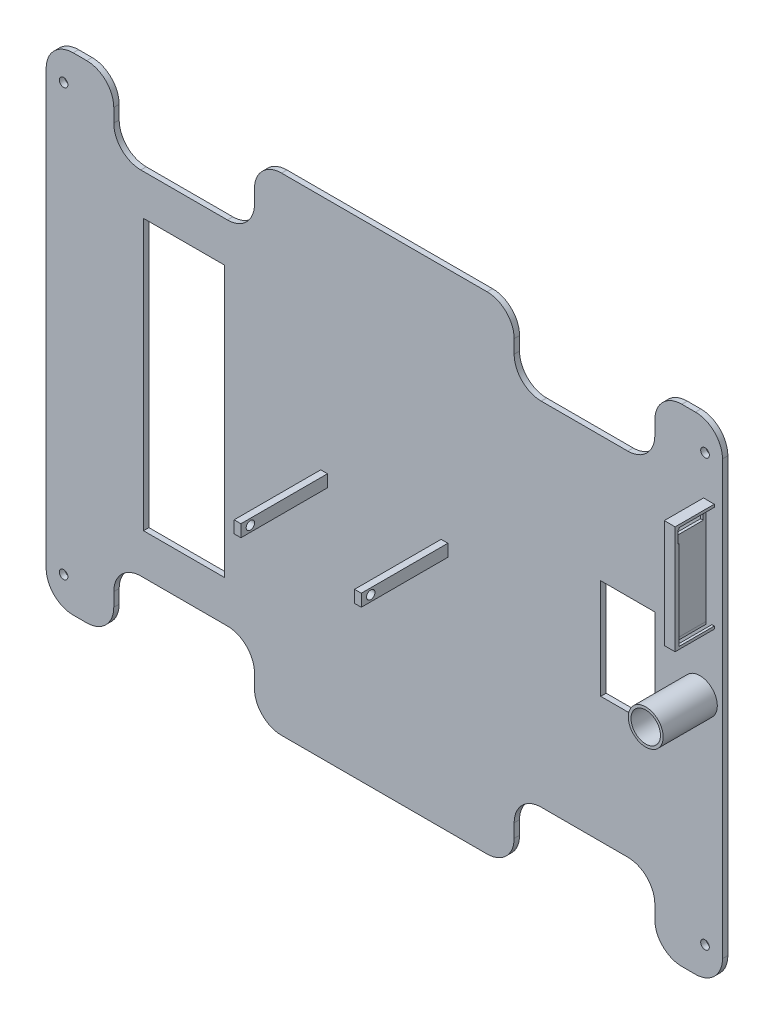
SolidWorks part; units mm, degrees
ref_plane "Plan de face" through (0, 0, 0) normal (0, 0, 1) x (1, 0, 0)
ref_plane "Plan de dessus" through (0, 0, 0) normal (0, 1, 0) x (1, 0, 0)
ref_plane "Plan de droite" through (0, 0, 0) normal (1, 0, 0) x (0, 0, -1)
sketch "Esquisse1" plane through (0, 0, 0) normal (0, 0, 1) x (1, 0, 0)
  line L0 (48, 77.5) -> (100, 77.5) construction
  line L1 (125, -90) -> (-125, -90)
  line L2 (125, -90) -> (125, 90)
  line L3 (125, 90) -> (-125, 90)
  line L4 (-125, -90) -> (-125, 90)
  line L5 (0, 90) -> (0, -90) construction
  line L6 (125, 0) -> (-125, 0) construction
  line L7 (-48, 65) -> (-100, 65)
  line L8 (-48, 65) -> (-48, 90)
  line L9 (-48, 90) -> (-100, 90)
  line L10 (-100, 65) -> (-100, 90)
  line L11 (-74, 90) -> (-74, 65) construction
  line L12 (-48, 77.5) -> (-100, 77.5) construction
  line L13 (74, 90) -> (74, 65) construction
  line L14 (100, 65) -> (100, 90)
  line L15 (48, 90) -> (100, 90)
  line L16 (48, 65) -> (48, 90)
  line L17 (48, 65) -> (100, 65)
  line L18 (74, -90) -> (74, -65) construction
  line L19 (-48, -77.5) -> (-100, -77.5) construction
  line L20 (-74, -90) -> (-74, -65) construction
  line L21 (48, -77.5) -> (100, -77.5) construction
  line L22 (48, -65) -> (100, -65)
  line L23 (48, -65) -> (48, -90)
  line L24 (48, -90) -> (100, -90)
  line L25 (100, -65) -> (100, -90)
  line L26 (-100, -65) -> (-100, -90)
  line L27 (-48, -90) -> (-100, -90)
  line L28 (-48, -65) -> (-48, -90)
  line L29 (-48, -65) -> (-100, -65)
  point P0 (0, 0)
  point P4 (-74, 77.5)
  point P16 (74, 77.5)
  point P33 (74, -77.5)
  point P34 (-74, -77.5)
  dimension "D1" = 250
  dimension "D2" = 180
  dimension "D3" = 52
  dimension "D4" = 25
  dimension "D5" = 25
extrude "Boss.-Extru.1" add sketch "Esquisse1" against normal blind 2 contours L2 L1 L4 L3 | L8 L7 L10 L9 | L14 L15 L16 L17 | L22 L25 L24 L23 | L26 L27 L28 L29
sketch "Esquisse2" plane through (0, 0, -2) normal (0, 0, -1) x (-1, 0, 0)
  line L1 (118.55, -78.76) -> (-118.55, -78.76) construction
  line L2 (118.55, -78.76) -> (118.55, 78.76) construction
  line L3 (118.55, 78.76) -> (-118.55, 78.76) construction
  line L4 (-118.55, -78.76) -> (-118.55, 78.76) construction
  line L5 (0, 78.76) -> (0, -78.76) construction
  line L6 (118.55, 0) -> (-118.55, 0) construction
  circle A0 centre (-118.55, 78.76) radius 1.6
  circle A1 centre (118.55, 78.76) radius 1.6
  circle A2 centre (118.55, -78.76) radius 1.6
  circle A3 centre (-118.55, -78.76) radius 1.6
  point P0 (0, 0)
  dimension "D3" = 3.2
  dimension "D1" = 237.1
  dimension "D2" = 157.52
extrude "Enlèv. mat.-Extru.1" cut sketch "Esquisse2" against normal through all
fillet "Congé1" radius 10 20 edges at (48, -90, -1) (48, -65, -1) (100, -65, -1) (100, -90, -1) (125, -90, -1) (125, 90, -1) (100, 90, -1) (100, 65, -1) (48, 65, -1) (48, 90, -1) (-48, 90, -1) (-48, 65, -1) (-100, 65, -1) (-100, 90, -1) (-125, -90, -1) (-100, -90, -1) (-100, -65, -1) (-48, -65, -1) (-48, -90, -1) (-125, 90, -1)
sketch "Esquisse3" plane through (0, 0, -2) normal (0, 0, -1) x (-1, 0, 0)
  circle A0 centre (122.8572, 0) radius 4.95
  dimension "D1" = 9.9
sketch "Esquisse5" plane through (0, 0, -2) normal (0, 0, -1) x (-1, 0, 0)
  line L0 (-125, -80) -> (-125, 80) construction
  line L1 (-80, -18.5) -> (-100, -18.5)
  line L2 (-80, -18.5) -> (-80, 18.5)
  line L3 (-80, 18.5) -> (-100, 18.5)
  line L4 (-100, -18.5) -> (-100, 18.5)
  line L5 (-90, 18.5) -> (-90, -18.5) construction
  line L6 (-80, 0) -> (-100, 0) construction
  point P0 (-90, 0)
  dimension "D1" = 37
  dimension "D2" = 20
  dimension "D3" = 35
extrude "Enlèv. mat.-Extru.4" cut sketch "Esquisse5" against normal blind 10
sketch "Esquisse6" plane through (0, 0, 0) normal (0, 0, 1) x (1, 0, 0)
  line L0 (125, -80) -> (125, 80) construction
  line L1 (122, 24) -> (118, 24)
  line L2 (122, 24) -> (122, 64)
  line L3 (122, 64) -> (118, 64)
  line L4 (118, 24) -> (118, 64)
  line L5 (120, 64) -> (120, 24) construction
  line L6 (122, 44) -> (118, 44) construction
  line L7 (58, 65) -> (90, 65) construction
  point P0 (120, 44)
  dimension "D1" = 40
  dimension "D2" = 4
  dimension "D3" = 5
  dimension "D4" = 1
extrude "Boss.-Extru.3" add sketch "Esquisse6" along normal blind 14.5
sketch "Esquisse9" plane through (122, 0, 0) normal (1, 0, 0) x (0, 0, -1)
  line L0 (-14.5, 24) -> (-14.5, 64) construction
  line L1 (0, 63) -> (-13, 63)
  line L2 (0, 63) -> (0, 25)
  line L3 (0, 25) -> (-13, 25)
  line L4 (-13, 63) -> (-13, 25)
  line L5 (-6.5, 25) -> (-6.5, 63) construction
  line L6 (0, 44) -> (-13, 44) construction
  line L7 (0, 24) -> (0, 64) construction
  point P0 (-6.5, 44)
  point P6 (-14.5, 44)
  point P7 (-7.25, 0.5)
  point P8 (-6.577, 0.5)
  point P9 (0, 0)
  point P12 (-7.25, 0.5)
  point P13 (-7.25, 0.5)
  point P14 (-7.25, 0.5)
  dimension "D1" = 38
  dimension "D2" = 1.5
sketch "Esquisse10" plane through (122, 0, 0) normal (1, 0, 0) x (0, 0, -1)
  line L0 (-14.5, 64) -> (0, 64) construction
  line L1 (-1.1, 57.9) -> (-13.4, 57.9)
  line L2 (-1.1, 57.9) -> (-1.1, 62.4)
  line L3 (-1.1, 62.4) -> (-13.4, 62.4)
  line L4 (-13.4, 57.9) -> (-13.4, 62.4)
  line L5 (-7.25, 62.4) -> (-7.25, 57.9) construction
  line L6 (-1.1, 60.15) -> (-13.4, 60.15) construction
  point P0 (-7.25, 60.15)
  point P6 (-7.25, 64)
  dimension "D1" = 12.3
  dimension "D2" = 38.4
  dimension "D3" = 4.5
  dimension "D4" = 3.85
extrude "Enlèv. mat.-Extru.5" cut sketch "Esquisse10" against normal blind 12.1 contours L1 L4 L3 L2
extrude "Enlèv. mat.-Extru.6" cut sketch "Esquisse9" against normal blind 3 contours L4 L3 L2 L1
sketch "Esquisse11" plane through (0, 25, 0) normal (0, 1, 0) x (1, 0, 0)
  line L0 (122, -14.5) -> (118, -14.5) construction
  line L1 (121.1, -13) -> (118.9, -13)
  line L2 (121.1, -13) -> (121.1, 0)
  line L3 (121.1, 0) -> (118.9, 0)
  line L4 (118.9, -13) -> (118.9, 0)
  line L5 (120, 0) -> (120, -13) construction
  line L6 (121.1, -6.5) -> (118.9, -6.5) construction
  line L7 (122, 0) -> (118, 0) construction
  point P0 (120, -6.5)
  point P6 (120, -14.5)
  point P7 (120, -6.6409)
  dimension "D1" = 13
  dimension "D2" = 2.2
extrude "Enlèv. mat.-Extru.7" cut sketch "Esquisse11" against normal blind 3
sketch "Esquisse14" plane through (0, 0, 0) normal (0, 0, 1) x (1, 0, 0)
  circle A0 centre (116.6445, 0) radius 6.45
  dimension "D1" = 12.9
extrude "Boss.-Extru.4" add sketch "Esquisse14" along normal blind 20
sketch "Esquisse15" plane through (0, 0, 20) normal (0, 0, 1) x (1, 0, 0)
  circle A0 centre (116.6445, 0) radius 5.45
  circle A1 centre (116.6445, 0) radius 6.45
  circle A2 centre (116.6445, 0) radius 6.45
  dimension "D1" = 0
  dimension "D2" = 1
extrude "Enlèv. mat.-Extru.8" cut sketch "Esquisse15" against normal through all contours A0
sketch "Esquisse17" plane through (0, 0, 0) normal (0, 0, 1) x (1, 0, 0)
  line L0 (-58, 65) -> (-90, 65) construction
  line L1 (-59, -50) -> (-89, -50)
  line L2 (-59, -50) -> (-59, 50)
  line L3 (-59, 50) -> (-89, 50)
  line L4 (-89, -50) -> (-89, 50)
  line L5 (-74, 50) -> (-74, -50) construction
  line L6 (-59, 0) -> (-89, 0) construction
  point P0 (-74, 0)
  point P6 (-74, 65)
  dimension "D1" = 100
  dimension "D2" = 30
extrude "Enlèv. mat.-Extru.10" cut sketch "Esquisse17" against normal through all
sketch "Esquisse18" plane through (0, 0, 0) normal (0, 0, 1) x (1, 0, 0)
  line L0 (21, 0) -> (23.5, 0) construction
  line L5 (0, 2) -> (0, -2) construction
  line L6 (22.25, 0) -> (-22.25, 0) construction
  line L7 (-21, -2.25) -> (-23.5, -2.25)
  line L8 (-21, -2.25) -> (-21, 2.25)
  line L9 (-21, 2.25) -> (-23.5, 2.25)
  line L10 (-23.5, -2.25) -> (-23.5, 2.25)
  line L11 (-22.25, 2.25) -> (-22.25, -2.25) construction
  line L12 (-21, 0) -> (-23.5, 0) construction
  line L13 (22.25, 2.25) -> (22.25, -2.25) construction
  line L14 (23.5, -2.25) -> (23.5, 2.25)
  line L15 (21, 2.25) -> (23.5, 2.25)
  line L16 (21, -2.25) -> (21, 2.25)
  line L17 (21, -2.25) -> (23.5, -2.25)
  point P0 (0, 0)
  dimension "D1" = 2.5
  dimension "D2" = 4.5
extrude "Boss.-Extru.5" add sketch "Esquisse18" along normal blind 32
sketch "Esquisse19" plane through (23.5, 0, 0) normal (1, 0, 0) x (0, 0, -1)
  line L0 (0, -2.25) -> (0, 2.25) construction
  circle A0 centre (-28.5, 0) radius 1.55
  dimension "D1" = 3.1
  dimension "D2" = 28.5
extrude "Enlèv. mat.-Extru.11" cut sketch "Esquisse19" against normal through all contours A0
